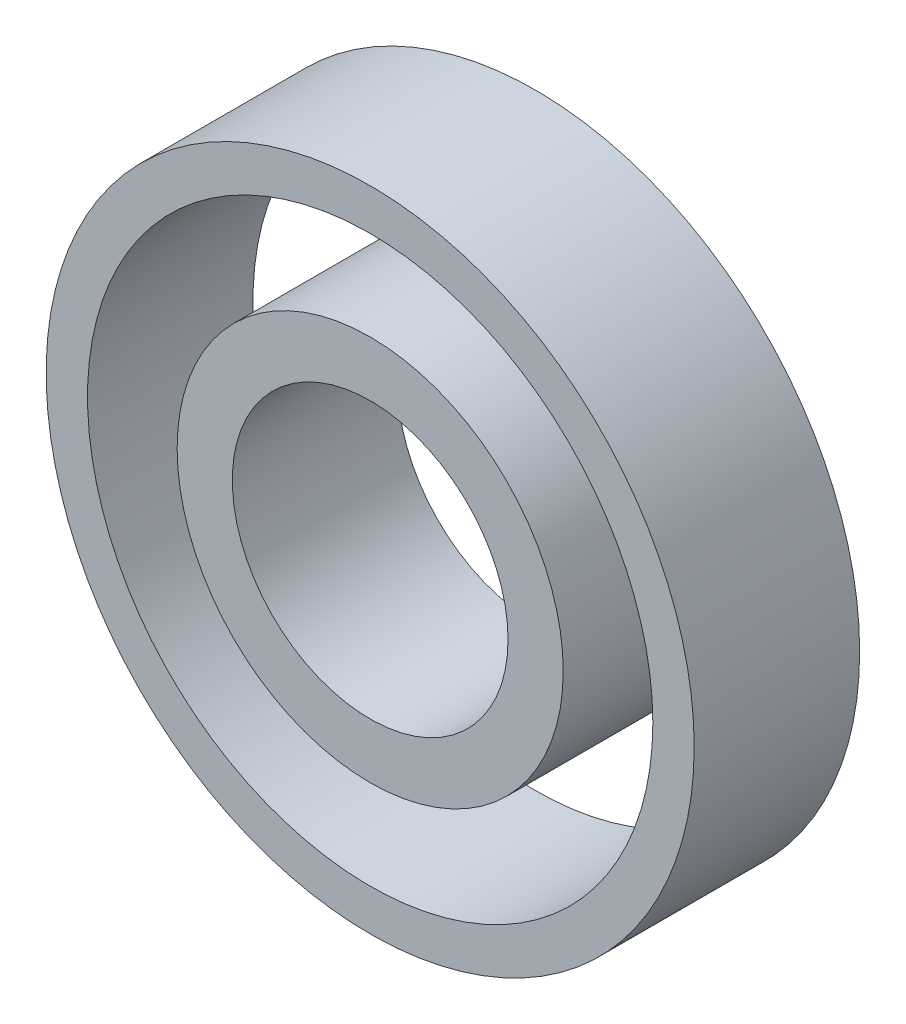
SolidWorks part; units mm, degrees
ref_plane "Front Plane" through (0, 0, 0) normal (0, 0, 1) x (1, 0, 0)
ref_plane "Top Plane" through (0, 0, 0) normal (0, 1, 0) x (1, 0, 0)
ref_plane "Right Plane" through (0, 0, 0) normal (1, 0, 0) x (0, 0, -1)
sketch "Sketch1" plane through (0, 0, 0) normal (0, 0, 1) x (1, 0, 0)
  circle A0 centre (0, 0) radius 23.5
  circle A1 centre (0, 0) radius 20.5
  dimension "D1" = 47
  dimension "D2" = 3
extrude "Boss-Extrude1" add sketch "Sketch1" along normal blind 12
sketch "Sketch2" plane through (0, 0, 12) normal (0, 0, 1) x (1, 0, 0)
  circle A0 centre (0, 0) radius 10
  circle A1 centre (0, 0) radius 14
  dimension "D1" = 20
  dimension "D2" = 28
extrude "Boss-Extrude2" add sketch "Sketch2" against normal blind 12 separate body
sketch "Sketch3" plane through (0, 0, 12) normal (0, 0, 1) x (1, 0, 0)
  circle A1 centre (0, 0) radius 14 construction
  circle A2 centre (0, 0) radius 20.5 construction
  circle A3 centre (0, 0) radius 14
  circle A4 centre (0, 0) radius 20.5
  dimension "D1" = 28
sketch "Sketch4" plane through (0, 0, 12) normal (0, 0, 1) x (1, 0, 0)
  circle A0 centre (0, 0) radius 14 construction
  circle A1 centre (0, 0) radius 20.5 construction
  circle A2 centre (0, 0) radius 14
  circle A3 centre (0, 0) radius 20.5
